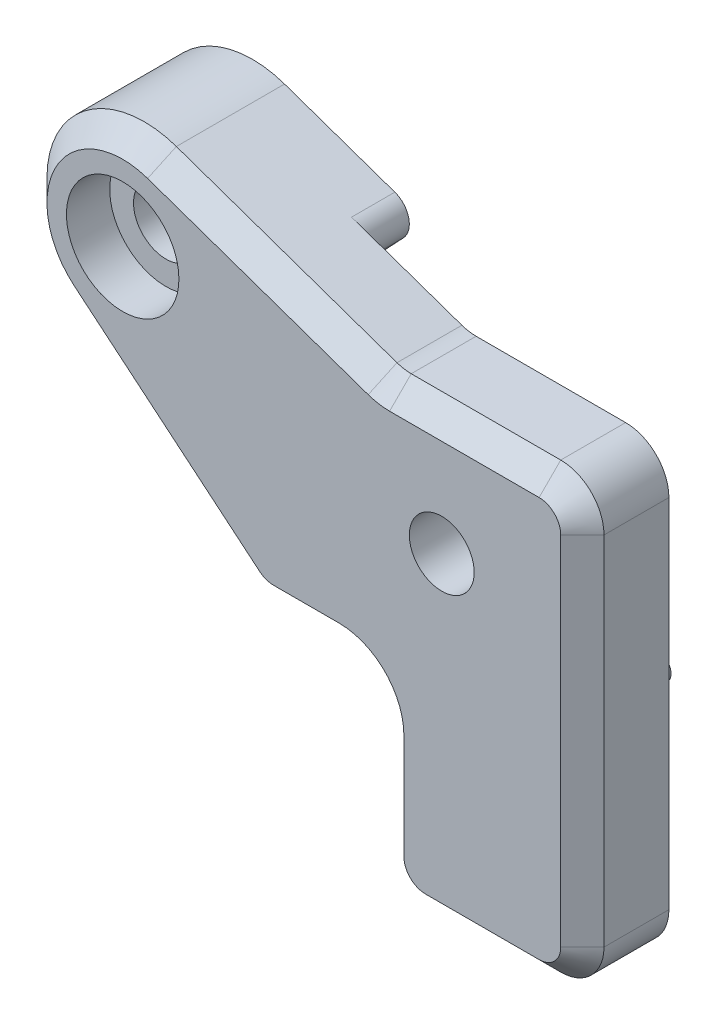
SolidWorks part; units mm, degrees
ref_plane "Front Plane" through (0, 0, 0) normal (0, 0, 1) x (1, 0, 0)
ref_plane "Top Plane" through (0, 0, 0) normal (0, 1, 0) x (1, 0, 0)
ref_plane "Right Plane" through (0, 0, 0) normal (1, 0, 0) x (0, 0, -1)
sketch "Sketch1" plane through (0, 0, 0) normal (0, 0, 1) x (1, 0, 0)
  line L0 (-2.75, -15) -> (-2.75, -6.15)
  line L1 (6.5, -15) -> (-2.75, -15)
  line L2 (6.5, -15) -> (6.5, 5.5)
  line L3 (6.5, 5.5) -> (-2.75, 5.5)
  line L7 (-13.2679, 9.1688) -> (-2.75, 5.5)
  line L8 (6.5, 5.5) -> (6.5, -15) construction
  line L9 (-2.75, 5.5) -> (6.5, 5.5) construction
  line L10 (-2.75, -6.15) -> (-2.75, -15) construction
  line L11 (6.5, -15) -> (-2.75, -15) construction
  line L12 (-2.75, -6.15) -> (-2.75, 5.5) construction
  line L13 (-17.6317, 1.4636) -> (-8.5, -6.15)
  line L14 (-8.5, -6.15) -> (-2.75, -6.15)
  line L15 (-2.75, -6.15) -> (-8.5, -6.15) construction
  line L16 (-16.25, 4.9199) -> (-19.25, 4.9199) construction
  circle A0 centre (0, 0) radius 1.25 construction
  circle A1 centre (0, 0) radius 1.5
  circle A2 centre (-14.75, 4.9199) radius 1.5
  arc A3 (-15.5, 3.6208) -> (-15.5, 6.2189) centre (-14.75, 4.9199) ccw construction
  arc A4 (-13.2679, 9.1688) -> (-17.6317, 1.4636) centre (-14.75, 4.9199) ccw
  dimension "D2" = 2.5
  dimension "D3" = 3
  dimension "D1" = 0.25
extrude "Boss-Extrude1" add sketch "Sketch1" against normal blind 2
fillet "Fillet1" radius 2 6 edges at (6.5, -15, -1) (-8.5, -6.15, -1) (-2.75, 5.5, -1) (6.5, 5.5, -1) (-2.75, -15, -1) (-2.75, -6.15, -1)
sketch "Sketch2" plane through (0, 0, 0) normal (0, 0, 1) x (1, 0, 0)
  line L7 (-0.75, -15) -> (4.5, -15)
  line L8 (6.5, -13) -> (6.5, 3.5)
  line L9 (4.5, 5.5) -> (-2.4112, 5.5)
  line L10 (-3.0699, 5.6116) -> (-13.2679, 9.1688)
  line L11 (-17.6317, 1.4636) -> (-9.0564, -5.6861)
  line L12 (-7.7756, -6.15) -> (-4.75, -6.15)
  line L13 (-2.75, -8.15) -> (-2.75, -13)
  line L14 (-0.75, -15) -> (4.5, -15)
  line L15 (6.5, -13) -> (6.5, 3.5)
  line L16 (4.5, 5.5) -> (-2.4112, 5.5)
  line L17 (-3.0699, 5.6116) -> (-13.2679, 9.1688)
  line L18 (-17.6317, 1.4636) -> (-9.0564, -5.6861)
  line L19 (-7.7756, -6.15) -> (-4.75, -6.15)
  line L20 (-2.75, -8.15) -> (-2.75, -13)
  circle A0 centre (0, 0) radius 1.5 construction
  circle A1 centre (0, 0) radius 1.5
  circle A2 centre (-14.75, 4.9199) radius 2.35 construction
  circle A3 centre (-14.75, 4.9199) radius 1.5 construction
  circle A4 centre (-14.75, 4.9199) radius 2.6
  arc A7 (4.5, -15) -> (6.5, -13) centre (4.5, -13) ccw
  arc A8 (6.5, 3.5) -> (4.5, 5.5) centre (4.5, 3.5) ccw
  arc A9 (-3.0699, 5.6116) -> (-2.4112, 5.5) centre (-2.4112, 7.5) ccw
  arc A10 (-13.2679, 9.1688) -> (-17.6317, 1.4636) centre (-14.75, 4.9199) ccw
  arc A11 (-9.0564, -5.6861) -> (-7.7756, -6.15) centre (-7.7756, -4.15) ccw
  arc A12 (-2.75, -8.15) -> (-4.75, -6.15) centre (-4.75, -8.15) ccw
  arc A13 (-2.75, -13) -> (-0.75, -15) centre (-0.75, -13) ccw
  arc A14 (4.5, -15) -> (6.5, -13) centre (4.5, -13) ccw
  arc A15 (6.5, 3.5) -> (4.5, 5.5) centre (4.5, 3.5) ccw
  arc A16 (-3.0699, 5.6116) -> (-2.4112, 5.5) centre (-2.4112, 7.5) ccw
  arc A17 (-13.2679, 9.1688) -> (-17.6317, 1.4636) centre (-14.75, 4.9199) ccw
  arc A18 (-9.0564, -5.6861) -> (-7.7756, -6.15) centre (-7.7756, -4.15) ccw
  arc A19 (-2.75, -8.15) -> (-4.75, -6.15) centre (-4.75, -8.15) ccw
  arc A20 (-2.75, -13) -> (-0.75, -15) centre (-0.75, -13) ccw
  dimension "D3" = 4.7
extrude "Boss-Extrude2" add sketch "Sketch2" along normal blind 2
chamfer "Chamfer1" distance 1 angle 45 14 edges at (1.875, -15, 2) (5.9142, -14.4142, 2) (-2.1642, -14.4142, 2) (6.5, -4.75, 2) (-2.75, -10.575, 2) (5.9142, 4.9142, 2) (-3.3358, -6.7358, 2) (1.0444, 5.5, 2) (-6.2628, -6.15, 2) (-2.7452, 5.5281, 2) (-8.4567, -6.0305, 2) (-8.1689, 7.3902, 2) (-13.344, -2.1113, 2) (-18.6656, 7.1375, 2)
sketch "Sketch3" plane through (0, 0, -2) normal (0, 0, -1) x (-1, 0, 0)
  line L0 (0, 0) -> (0, -9.5) construction
  circle A0 centre (0, -9.5) radius 1.25 construction
  circle A1 centre (0, -9.5) radius 1
  dimension "D3" = 2.5
  dimension "D1" = 9.5
extrude "Boss-Extrude3" add sketch "Sketch3" along normal blind 6
chamfer "Chamfer2" distance 3.5 distance2 0.4 1 edges at (-1, -9.5, -8)
sketch "Sketch4" plane through (0, 0, -2) normal (0, 0, -1) x (-1, 0, 0)
  line L0 (13.2679, 9.1688) -> (8.1689, 7.3902)
  line L1 (7.7709, 5.7597) -> (11.4769, 1.8317)
  line L2 (3.0699, 5.6116) -> (13.2679, 9.1688) construction
  circle A0 centre (14.75, 4.9199) radius 1.5 construction
  circle A1 centre (14.75, 4.9199) radius 1.5
  arc A4 (11.4769, 1.8317) -> (13.2679, 9.1688) centre (14.75, 4.9199) ccw
  arc A5 (17.6317, 1.4636) -> (13.2679, 9.1688) centre (14.75, 4.9199) ccw construction
  arc A6 (8.1689, 7.3902) -> (7.7709, 5.7597) centre (8.4983, 6.446) ccw
  dimension "D1" = 1
extrude "Boss-Extrude4" add sketch "Sketch4" along normal offset from surface (2 mm away) 6 up to face at (-3.0922, -3.4294, 2)
equation "\"Tolerance\" = 0.25mm"
equation "\"Pocket_Head_M5\"= 8mm"
equation "\"Pocket_Head_M4\" = 7mm"
equation "\"Pocket_Nut_M4\" = 7mm"
equation "\"Pocket_Nut_M5\"= 8mm"
equation "\"Pocket_Nut_M3\"= 5.5mm"
equation "\"Pocket_Head_M3\"= 5.5mm"
equation "\"D1@Sketch1\"=\"Tolerance\""
equation "\"D2@Sketch2\"=\"Tolerance\""
equation "\"Pocket_Head_M2.5\" = 4.7mm"
equation "\"D3@Sketch2\"=\"Pocket_Head_M2.5\""
equation "\"D2@Sketch3\"=\"Tolerance\""
